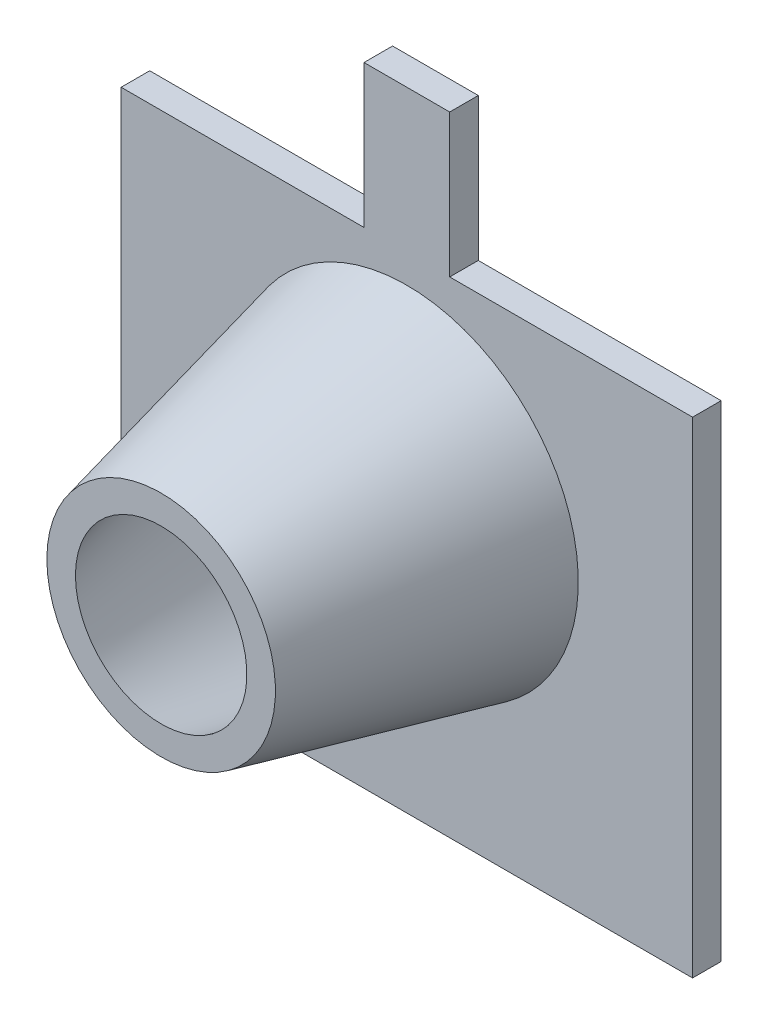
SolidWorks part; units mm, degrees
ref_plane "Front Plane" through (0, 0, 0) normal (0, 0, 1) x (1, 0, 0)
ref_plane "Top Plane" through (0, 0, 0) normal (0, 1, 0) x (1, 0, 0)
ref_plane "Right Plane" through (0, 0, 0) normal (1, 0, 0) x (0, 0, -1)
ref_plane "Plate Base y1.95" through (0, 1.95, 0) normal (0, 1, 0) x (1, 0, 0)
sketch "Minus Plate 10 x 8.5 x 0.5 Sketch" plane through (0, 1.95, 0) normal (0, 1, 0) x (1, 0, 0)
  line L0 (20.7, 64.85) -> (30.7, 64.85)
  line L1 (30.7, 64.85) -> (30.7, 65.35)
  line L2 (30.7, 65.35) -> (20.7, 65.35)
  line L3 (20.7, 65.35) -> (20.7, 64.85)
extrude "Minus Plate 10 x 8.5 x 0.5" add sketch "Minus Plate 10 x 8.5 x 0.5 Sketch" along normal blind 8.5
ref_plane "Plate Top y10.45" through (0, 10.45, 0) normal (0, 1, 0) x (1, 0, 0)
sketch "Solder Tab 1.5 x 2.5 Sketch" plane through (0, 10.45, 0) normal (0, 1, 0) x (1, 0, 0)
  line L0 (24.95, 64.85) -> (26.45, 64.85)
  line L1 (26.45, 64.85) -> (26.45, 65.35)
  line L2 (26.45, 65.35) -> (24.95, 65.35)
  line L3 (24.95, 65.35) -> (24.95, 64.85)
extrude "Solder Tab 1.5 x 2.5" add sketch "Solder Tab 1.5 x 2.5 Sketch" along normal blind 2.5
ref_plane "Contact Axis Plane y6.95" through (0, 6.95, 0) normal (0, 1, 0) x (1, 0, 0)
sketch "Spring (compressed 4.3) Sketch" plane through (0, 6.95, 0) normal (0, 1, 0) x (1, 0, 0)
  line L0 (25.7, 65.85) -> (25.7, 59.55) construction
  line L1 (28.2, 64.85) -> (28.7, 64.85)
  line L2 (28.7, 64.85) -> (27.7, 60.55)
  line L3 (27.7, 60.55) -> (27.2, 60.55)
  line L4 (27.2, 60.55) -> (28.2, 64.85)
revolve "Spring (compressed 4.3)" add sketch "Spring (compressed 4.3) Sketch" angle 360 about L0
